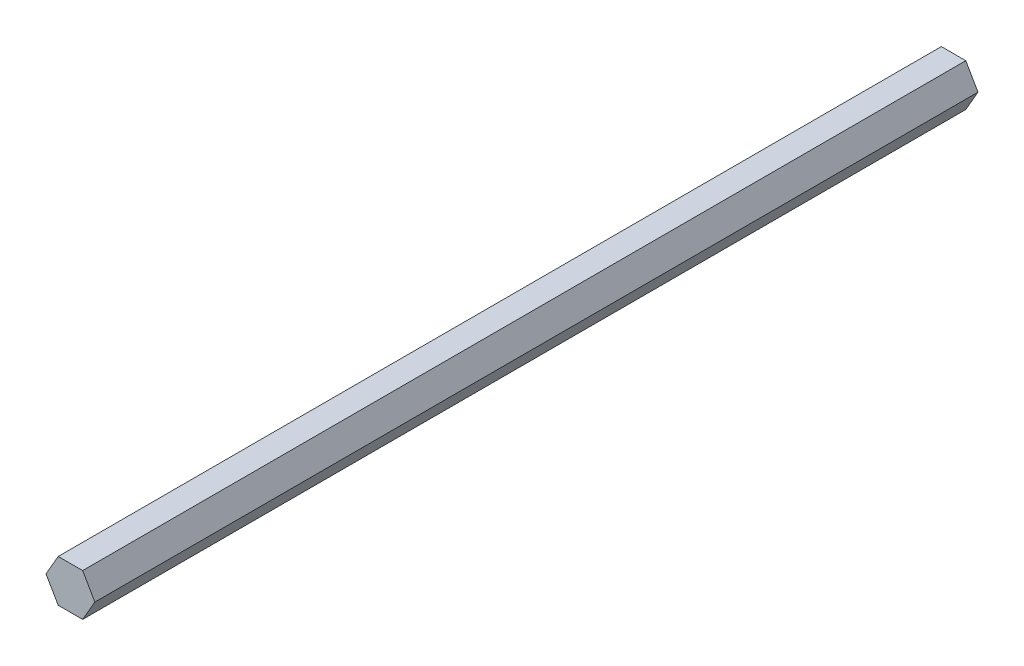
SolidWorks part; units mm, degrees
ref_plane "Front Plane" through (0, 0, 0) normal (0, 0, 1) x (1, 0, 0)
ref_plane "Top Plane" through (0, 0, 0) normal (0, 1, 0) x (1, 0, 0)
ref_plane "Right Plane" through (0, 0, 0) normal (1, 0, 0) x (0, 0, -1)
sketch "Sketch1" plane through (0, 0, 0) normal (0, 0, 1) x (1, 0, 0)
  line L1 (7.3323, 0) -> (3.6662, 6.35)
  line L2 (3.6662, 6.35) -> (-3.6662, 6.35)
  line L3 (-3.6662, 6.35) -> (-7.3323, 0)
  line L4 (-7.3323, 0) -> (-3.6662, -6.35)
  line L5 (-3.6662, -6.35) -> (3.6662, -6.35)
  line L6 (3.6662, -6.35) -> (7.3323, 0)
  circle A0 centre (0, 0) radius 6.35 construction
  point P1 (0, 0)
  dimension "D1" = 12.7
extrude "Boss-Extrude1" add sketch "Sketch1" along normal mid plane 265
